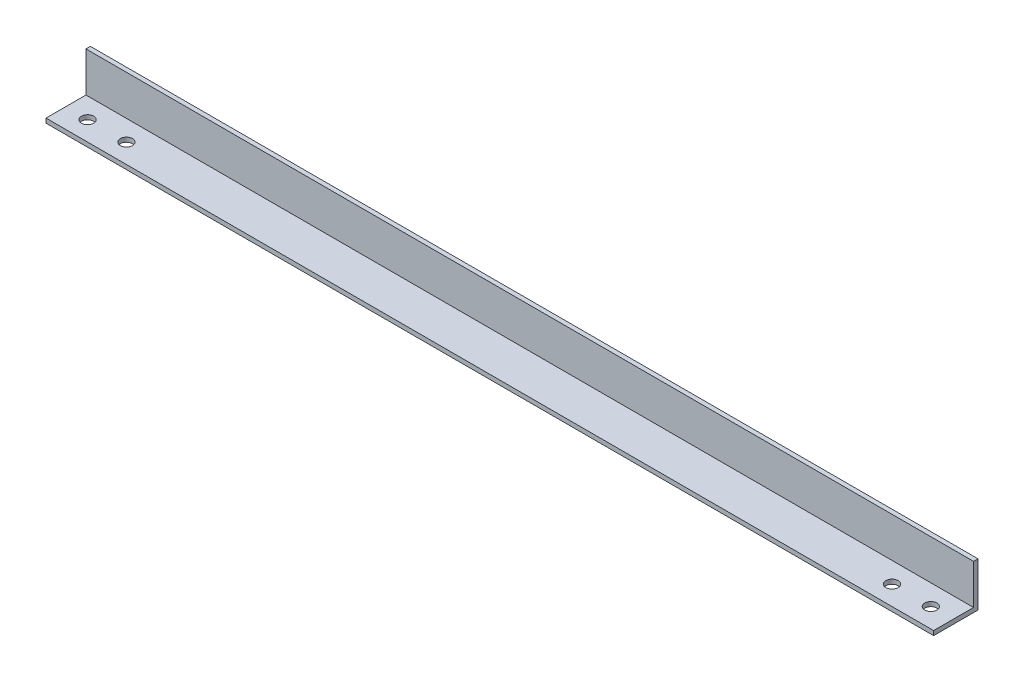
SolidWorks part; units mm, degrees
ref_plane "前视基准面" through (0, 0, 0) normal (0, 0, 1) x (1, 0, 0)
ref_plane "上视基准面" through (0, 0, 0) normal (0, 1, 0) x (1, 0, 0)
ref_plane "右视基准面" through (0, 0, 0) normal (1, 0, 0) x (0, 0, -1)
sketch "底面" plane through (0, 0, 0) normal (0, 0, 1) x (1, 0, 0)
  line L1 (0, 0) -> (1600, 0)
  line L2 (0, 0) -> (0, 80)
  line L3 (0, 80) -> (1600, 80)
  line L4 (1600, 0) -> (1600, 80)
  dimension "D1" = 1600
  dimension "D2" = 80
extrude "拉伸4" add sketch "底面" along normal blind 8
sketch "草图3" plane through (0, 0, 8) normal (0, 0, 1) x (1, 0, 0)
  line L1 (0, 0) -> (1600, 0)
  line L2 (0, 0) -> (0, 8)
  line L3 (0, 8) -> (1600, 8)
  line L4 (1600, 0) -> (1600, 8)
  dimension "D1" = 1600
  dimension "D2" = 8
extrude "拉伸5" add sketch "草图3" along normal blind 72
sketch "草图4" plane through (0, 8, 0) normal (0, 1, 0) x (1, 0, 0)
  line L1 (1600, -80) -> (0, -80) construction
  circle A0 centre (40, -45) radius 11
  circle A1 centre (110, -45) radius 11
  circle A2 centre (1490, -45) radius 11
  circle A3 centre (1560, -45) radius 11
  point P0 (800, -80)
  dimension "D1" = 760
  dimension "D4" = 1520
  dimension "D2" = 70
  dimension "D3" = 35
  dimension "D5" = 70
extrude "切除-拉伸2" cut sketch "草图4" against normal through all
